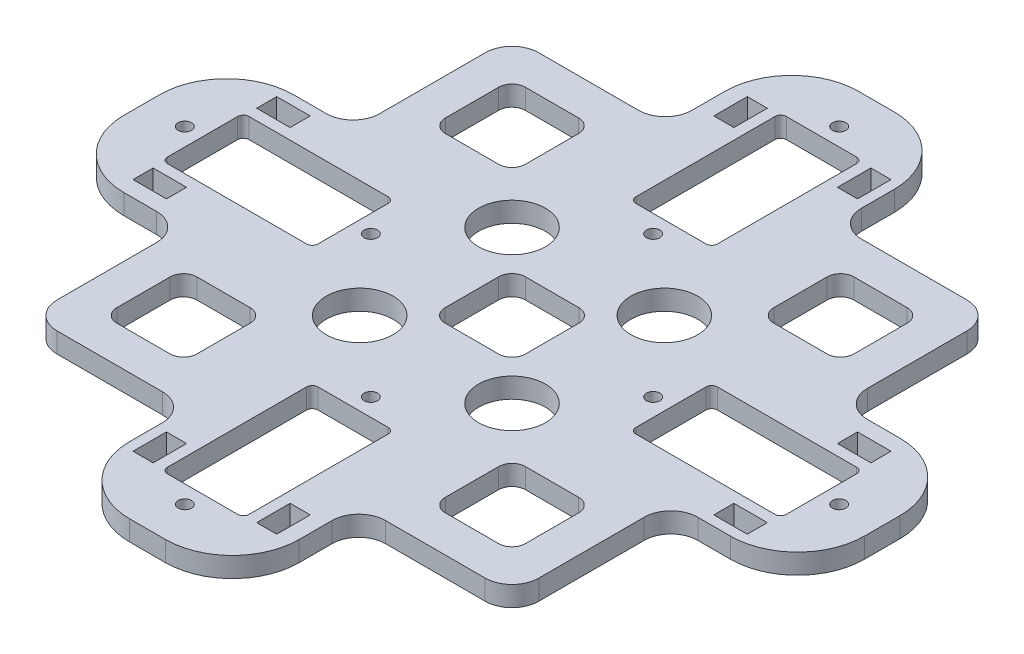
SolidWorks part; units mm, degrees
ref_plane "Front Plane" through (0, 0, 0) normal (0, 0, 1) x (1, 0, 0)
ref_plane "Top Plane" through (0, 0, 0) normal (0, 1, 0) x (1, 0, 0)
ref_plane "Right Plane" through (0, 0, 0) normal (1, 0, 0) x (0, 0, -1)
sketch "Sketch2" plane through (0, 0, 0) normal (0, 1, 0) x (1, 0, 0)
  line L0 (0, 35) -> (0, 46.25) construction
  line L1 (5.25, 23.75) -> (-5.25, 23.75)
  line L2 (6.1, 24.6) -> (6.1, 45.4)
  line L3 (5.25, 46.25) -> (-5.25, 46.25)
  line L4 (-6.1, 24.6) -> (-6.1, 45.4)
  line L5 (0, 35) -> (-6.1, 35) construction
  line L6 (18.1, -12.2377) -> (44.9, -12.2377)
  line L7 (12.5118, 15.9935) -> (-11.6882, 15.9935) construction
  line L8 (12.2377, 18.1) -> (12.2377, 44.9)
  line L9 (2.2377, 54.9) -> (-3.1, 54.9)
  line L10 (-13.1, 17.2377) -> (-13.1, 44.9)
  line L11 (12.5118, 15.9935) -> (-13.1, 54.9) construction
  line L12 (12.2377, 54.9) -> (-11.6882, 15.9935) construction
  line L13 (15.9935, -12.5118) -> (15.9935, 11.6882) construction
  line L14 (17.2377, 13.1) -> (44.9, 13.1)
  line L15 (54.9, -2.2377) -> (54.9, 3.1)
  line L16 (24.6, -6.1) -> (45.4, -6.1)
  line L17 (23.75, -5.25) -> (23.75, 5.25)
  line L18 (24.6, 6.1) -> (45.4, 6.1)
  line L19 (46.25, -5.25) -> (46.25, 5.25)
  line L20 (-12.2377, -18.1) -> (-12.2377, -44.9)
  line L21 (-12.5118, -15.9935) -> (11.6882, -15.9935) construction
  line L22 (13.1, -17.2377) -> (13.1, -44.9)
  line L23 (-2.2377, -54.9) -> (3.1, -54.9)
  line L24 (-6.1, -24.6) -> (-6.1, -45.4)
  line L25 (-5.25, -23.75) -> (5.25, -23.75)
  line L26 (6.1, -24.6) -> (6.1, -45.4)
  line L27 (-5.25, -46.25) -> (5.25, -46.25)
  line L28 (-18.1, 12.2377) -> (-44.9, 12.2377)
  line L29 (-15.9935, 12.5118) -> (-15.9935, -11.6882) construction
  line L30 (-17.2377, -13.1) -> (-44.9, -13.1)
  line L31 (-54.9, 2.2377) -> (-54.9, -3.1)
  line L32 (-24.6, 6.1) -> (-45.4, 6.1)
  line L33 (-23.75, 5.25) -> (-23.75, -5.25)
  line L34 (-24.6, -6.1) -> (-45.4, -6.1)
  line L35 (-46.25, 5.25) -> (-46.25, -5.25)
  line L36 (20.5609, 18.5609) -> (28.535, 18.5609)
  line L37 (4, -6) -> (-4, -6)
  line L38 (6, -4) -> (6, 4)
  line L39 (4, 6) -> (-4, 6)
  line L40 (-6, -4) -> (-6, 4)
  line L41 (6, -6) -> (-6, 6) construction
  line L42 (6, 6) -> (-6, -6) construction
  line L43 (36, -36) -> (13.1, -36)
  line L44 (36, -36) -> (36, -12.2377)
  line L45 (36, 36) -> (12.2377, 36)
  line L46 (-36, -36) -> (-36, -13.1)
  line L47 (36, -36) -> (-36, 36) construction
  line L48 (36, 36) -> (-36, -36) construction
  line L49 (-20.5609, 18.5609) -> (-28.535, 18.5609)
  line L50 (-18.5609, 20.5609) -> (-18.5609, 28.535)
  line L51 (-20.5609, 30.535) -> (-28.535, 30.535)
  line L52 (-30.535, 20.5609) -> (-30.535, 28.535)
  line L53 (-18.5609, 18.5609) -> (-30.535, 30.535) construction
  line L54 (-18.5609, 30.535) -> (-30.535, 18.5609) construction
  line L55 (18.5609, 20.5609) -> (18.5609, 28.535)
  line L56 (20.5609, 30.535) -> (28.535, 30.535)
  line L57 (30.535, 20.5609) -> (30.535, 28.535)
  line L58 (18.5609, -20.5609) -> (18.5609, -28.535)
  line L59 (20.5609, -18.5609) -> (28.535, -18.5609)
  line L60 (30.535, -20.5609) -> (30.535, -28.535)
  line L61 (20.5609, -30.535) -> (28.535, -30.535)
  line L62 (-20.5609, -18.5609) -> (-28.535, -18.5609)
  line L63 (-18.5609, -20.5609) -> (-18.5609, -28.535)
  line L64 (-20.5609, -30.535) -> (-28.535, -30.535)
  line L65 (-30.535, -20.5609) -> (-30.535, -28.535)
  line L66 (-36, 12.2377) -> (-36, 36)
  line L67 (-13.1, 36) -> (-36, 36)
  line L68 (-12.2377, -36) -> (-36, -36)
  line L69 (36, 13.1) -> (36, 36)
  circle A0 centre (0, 48.9) radius 1
  circle A1 centre (0, 21.1) radius 1
  circle A2 centre (48.9, 0) radius 1
  circle A3 centre (21.1, 0) radius 1
  circle A4 centre (0, -48.9) radius 1
  circle A5 centre (0, -21.1) radius 1
  circle A6 centre (-48.9, 0) radius 1
  circle A7 centre (-21.1, 0) radius 1
  arc A8 (-3.1, 54.9) -> (-13.1, 44.9) centre (-3.1, 44.9) ccw
  arc A9 (12.2377, 44.9) -> (2.2377, 54.9) centre (2.2377, 44.9) ccw
  arc A10 (44.9, 13.1) -> (54.9, 3.1) centre (44.9, 3.1) cw
  arc A11 (44.9, -12.2377) -> (54.9, -2.2377) centre (44.9, -2.2377) ccw
  arc A12 (13.1, -44.9) -> (3.1, -54.9) centre (3.1, -44.9) cw
  arc A13 (-2.2377, -54.9) -> (-12.2377, -44.9) centre (-2.2377, -44.9) cw
  arc A14 (-54.9, -3.1) -> (-44.9, -13.1) centre (-44.9, -3.1) ccw
  arc A15 (-44.9, 12.2377) -> (-54.9, 2.2377) centre (-44.9, 2.2377) ccw
  arc A16 (-13.1, 17.2377) -> (-18.1, 12.2377) centre (-18.1, 17.2377) cw
  arc A17 (12.2377, 18.1) -> (17.2377, 13.1) centre (17.2377, 18.1) ccw
  arc A18 (18.1, -12.2377) -> (13.1, -17.2377) centre (18.1, -17.2377) ccw
  arc A19 (-12.2377, -18.1) -> (-17.2377, -13.1) centre (-17.2377, -18.1) ccw
  arc A20 (-4, -6) -> (-6, -4) centre (-4, -4) cw
  arc A21 (4, -6) -> (6, -4) centre (4, -4) ccw
  arc A22 (6, 4) -> (4, 6) centre (4, 4) ccw
  arc A23 (-4, 6) -> (-6, 4) centre (-4, 4) ccw
  arc A24 (-5.25, 23.75) -> (-6.1, 24.6) centre (-5.25, 24.6) cw
  arc A25 (5.25, 23.75) -> (6.1, 24.6) centre (5.25, 24.6) ccw
  arc A26 (6.1, 45.4) -> (5.25, 46.25) centre (5.25, 45.4) ccw
  arc A27 (-5.25, 46.25) -> (-6.1, 45.4) centre (-5.25, 45.4) ccw
  arc A28 (6.1, -45.4) -> (5.25, -46.25) centre (5.25, -45.4) cw
  arc A29 (-6.1, -45.4) -> (-5.25, -46.25) centre (-5.25, -45.4) ccw
  arc A30 (-6.1, -24.6) -> (-5.25, -23.75) centre (-5.25, -24.6) cw
  arc A31 (5.25, -23.75) -> (6.1, -24.6) centre (5.25, -24.6) cw
  arc A32 (45.4, -6.1) -> (46.25, -5.25) centre (45.4, -5.25) ccw
  arc A33 (45.4, 6.1) -> (46.25, 5.25) centre (45.4, 5.25) cw
  arc A34 (23.75, 5.25) -> (24.6, 6.1) centre (24.6, 5.25) cw
  arc A35 (24.6, -6.1) -> (23.75, -5.25) centre (24.6, -5.25) cw
  arc A36 (-45.4, -6.1) -> (-46.25, -5.25) centre (-45.4, -5.25) cw
  arc A37 (-23.75, -5.25) -> (-24.6, -6.1) centre (-24.6, -5.25) cw
  arc A38 (-24.6, 6.1) -> (-23.75, 5.25) centre (-24.6, 5.25) cw
  arc A39 (-45.4, 6.1) -> (-46.25, 5.25) centre (-45.4, 5.25) ccw
  circle A40 centre (40.15, 0) radius 1.5 construction
  circle A41 centre (0, -40.15) radius 1.5 construction
  circle A42 centre (-40.15, 0) radius 1.5 construction
  circle A43 centre (0, 40.15) radius 1.5 construction
  arc A44 (-18.5609, 28.535) -> (-20.5609, 30.535) centre (-20.5609, 28.535) ccw
  arc A45 (-20.5609, 18.5609) -> (-18.5609, 20.5609) centre (-20.5609, 20.5609) ccw
  arc A46 (-28.535, 18.5609) -> (-30.535, 20.5609) centre (-28.535, 20.5609) cw
  arc A47 (-28.535, 30.535) -> (-30.535, 28.535) centre (-28.535, 28.535) ccw
  arc A48 (-20.5609, -18.5609) -> (-18.5609, -20.5609) centre (-20.5609, -20.5609) cw
  arc A49 (-28.535, -18.5609) -> (-30.535, -20.5609) centre (-28.535, -20.5609) ccw
  arc A50 (-28.535, -30.535) -> (-30.535, -28.535) centre (-28.535, -28.535) cw
  arc A51 (-18.5609, -28.535) -> (-20.5609, -30.535) centre (-20.5609, -28.535) cw
  arc A52 (18.5609, -28.535) -> (20.5609, -30.535) centre (20.5609, -28.535) ccw
  arc A53 (30.535, -28.535) -> (28.535, -30.535) centre (28.535, -28.535) cw
  arc A54 (18.5609, -20.5609) -> (20.5609, -18.5609) centre (20.5609, -20.5609) cw
  arc A55 (28.535, -18.5609) -> (30.535, -20.5609) centre (28.535, -20.5609) cw
  arc A56 (28.535, 30.535) -> (30.535, 28.535) centre (28.535, 28.535) cw
  arc A57 (28.535, 18.5609) -> (30.535, 20.5609) centre (28.535, 20.5609) ccw
  arc A58 (20.5609, 18.5609) -> (18.5609, 20.5609) centre (20.5609, 20.5609) cw
  arc A59 (18.5609, 28.535) -> (20.5609, 30.535) centre (20.5609, 28.535) cw
  point P0 (0, 35)
  point P83 (0, 0)
  point P102 (-6.1, 23.75)
  point P107 (6.1, 46.25)
  point P110 (-6.1, 46.25)
  point P137 (0, 0)
  point P148 (-24.548, 24.548)
  dimension "D3" = 2
  dimension "D9" = 10
  dimension "D10" = 5
  dimension "D13" = 2
  dimension "D14" = 0.85
  dimension "D15" = 0.85
  dimension "D16" = 3
  dimension "D23" = 2
  dimension "D24" = 2
  dimension "D1" = 22.5
  dimension "D2" = 12.2
  dimension "D4" = 27.8
  dimension "D5" = 35
  dimension "D6" = 7
  dimension "D7" = 6
  dimension "D11" = 12
  dimension "D12" = 12
  dimension "D17" = 16.4
  dimension "D19" = 72
  dimension "D20" = 72
  dimension "D21" = 5.465
  dimension "D22" = 4
  dimension "D8" = 4
  dimension "D18" = 4
extrude "Boss-Extrude1" add sketch "Sketch2" along normal blind 3 contours A19 L20 A13 L23 A12 L22 A18 L6 A11 L15 A10 L14 A17 L8 A9 L9 A8 L10 A16 L28 A15 L31 A14 L30 A39 L32 A38 L33 A37 L34 A36 L35 A27 L3 A26 L2 A25 L1 A24 L4 | A16 L10 L67 L66 L28 L49 L52 L51 L50 | L8 A17 L14 L69 L45 L57 L36 L55 L56 | L6 A18 L22 L43 L44 L61 L58 L59 L60 | L20 A19 L30 L46 L68 L65 L62 L63 L64
fillet "Fillet1" radius 4 12 edges at (-36, 1.5, -12.2377) (-36, 1.5, -36) (-13.1, 1.5, -36) (12.2377, 1.5, -36) (36, 1.5, -36) (36, 1.5, -13.1) (36, 1.5, 12.2377) (36, 1.5, 36) (13.1, 1.5, 36) (-36, 1.5, 13.1) (-12.2377, 1.5, 36) (-36, 1.5, 36)
sketch "Sketch4" plane through (0, 3, 0) normal (0, 1, 0) x (1, 0, 0)
  line L0 (0, 0) -> (15.0691, 0) construction
  line L1 (-11.3828, 11.3828) -> (0, 0) construction
  circle A0 centre (-11.3828, 11.3828) radius 5
  circle A1 centre (11.3828, 11.3828) radius 5
  circle A2 centre (11.3828, -11.3828) radius 5
  circle A3 centre (-11.3828, -11.3828) radius 5
  dimension "D1" = 10
  dimension "D2" = 135
  dimension "D3" = 4
extrude "Cut-Extrude1" cut sketch "Sketch4" against normal up to surface (3 mm away) up to face at (0, 0, 0)
sketch "Sketch5" plane through (0, 3, 0) normal (0, 1, 0) x (1, 0, 0)
  line L0 (-40, 12.2377) -> (-44.9, 12.2377) construction
  line L1 (-45.9, 7.7377) -> (-40.9, 7.7377)
  line L2 (-45.9, 7.7377) -> (-45.9, 10.7377)
  line L3 (-45.9, 10.7377) -> (-40.9, 10.7377)
  line L4 (-40.9, 7.7377) -> (-40.9, 10.7377)
  line L5 (-54.9, 2.2377) -> (-54.9, -3.1) construction
  line L6 (-46.25, 0) -> (-23.75, 0) construction
  line L7 (-46.25, 5.25) -> (-46.25, -5.25) construction
  line L8 (-23.75, 5.25) -> (-23.75, -5.25) construction
  line L9 (-45.9, -10.7377) -> (-40.9, -10.7377)
  line L10 (-40.9, -7.7377) -> (-40.9, -10.7377)
  line L11 (-45.9, -7.7377) -> (-40.9, -7.7377)
  line L12 (-45.9, -7.7377) -> (-45.9, -10.7377)
  line L13 (7.7377, 45.9) -> (10.7377, 45.9)
  line L14 (7.7377, 45.9) -> (7.7377, 40.9)
  line L15 (7.7377, 40.9) -> (10.7377, 40.9)
  line L16 (10.7377, 45.9) -> (10.7377, 40.9)
  line L17 (-10.7377, 45.9) -> (-10.7377, 40.9)
  line L18 (-7.7377, 40.9) -> (-10.7377, 40.9)
  line L19 (-7.7377, 45.9) -> (-7.7377, 40.9)
  line L20 (-7.7377, 45.9) -> (-10.7377, 45.9)
  line L21 (45.9, -7.7377) -> (45.9, -10.7377)
  line L22 (45.9, -7.7377) -> (40.9, -7.7377)
  line L23 (40.9, -7.7377) -> (40.9, -10.7377)
  line L24 (45.9, -10.7377) -> (40.9, -10.7377)
  line L25 (45.9, 10.7377) -> (40.9, 10.7377)
  line L26 (40.9, 7.7377) -> (40.9, 10.7377)
  line L27 (45.9, 7.7377) -> (40.9, 7.7377)
  line L28 (45.9, 7.7377) -> (45.9, 10.7377)
  line L29 (-7.7377, -45.9) -> (-10.7377, -45.9)
  line L30 (-7.7377, -45.9) -> (-7.7377, -40.9)
  line L31 (-7.7377, -40.9) -> (-10.7377, -40.9)
  line L32 (-10.7377, -45.9) -> (-10.7377, -40.9)
  line L33 (10.7377, -45.9) -> (10.7377, -40.9)
  line L34 (7.7377, -40.9) -> (10.7377, -40.9)
  line L35 (7.7377, -45.9) -> (7.7377, -40.9)
  line L36 (7.7377, -45.9) -> (10.7377, -45.9)
  point P4 (-43.4, 10.7377)
  dimension "D1" = 3
  dimension "D2" = 1.5
  dimension "D3" = 9
  dimension "D4" = 5
  dimension "D5" = 4
extrude "Cut-Extrude2" cut sketch "Sketch5" against normal up to surface (3 mm away) up to face at (-11.3828, 0, 16.3828)
